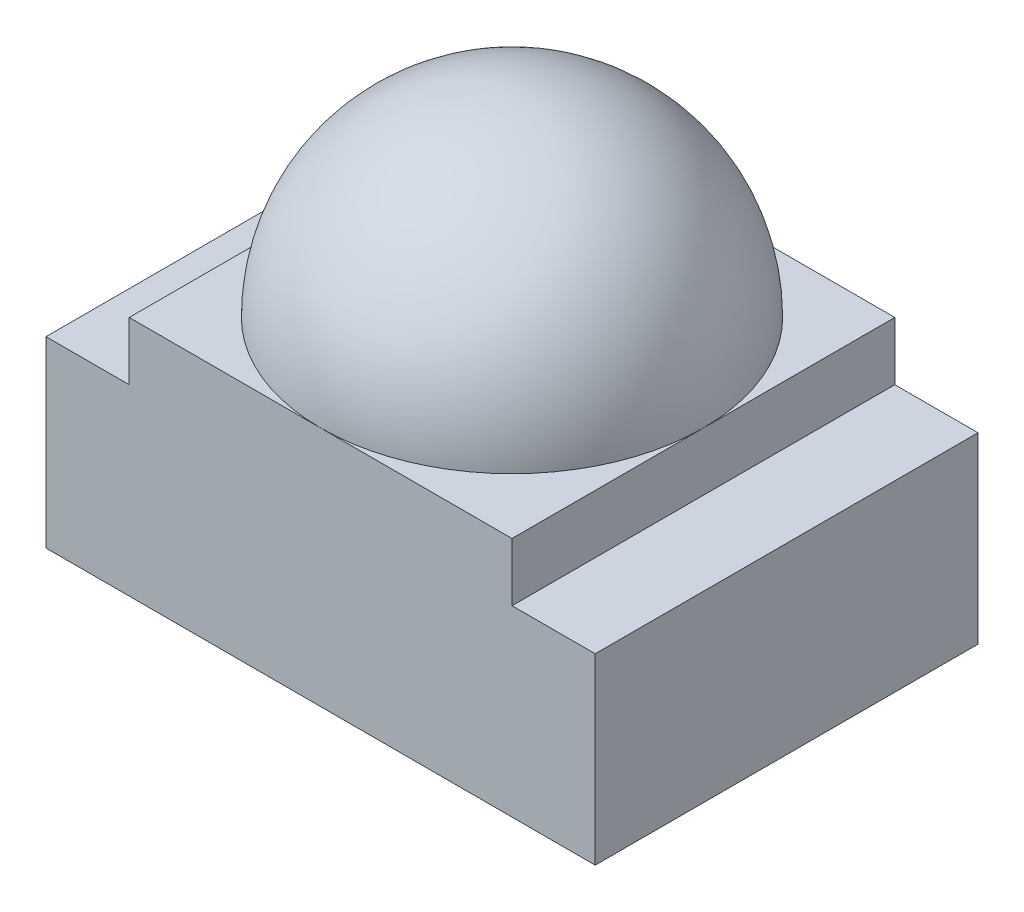
SolidWorks part; units mm, degrees
ref_plane "Front Plane" through (0, 0, 0) normal (0, 0, 1) x (1, 0, 0)
ref_plane "Top Plane" through (0, 0, 0) normal (0, 1, 0) x (1, 0, 0)
ref_plane "Right Plane" through (0, 0, 0) normal (1, 0, 0) x (0, 0, -1)
sketch "Sketch1" plane through (0, 0, 0) normal (0, 1, 0) x (1, 0, 0)
  line L1 (-16.5, 11.5) -> (16.5, 11.5)
  line L2 (-16.5, 11.5) -> (-16.5, -11.5)
  line L3 (-16.5, -11.5) -> (16.5, -11.5)
  line L4 (16.5, 11.5) -> (16.5, -11.5)
  line L5 (-16.5, 11.5) -> (16.5, -11.5) construction
  line L6 (-16.5, -11.5) -> (16.5, 11.5) construction
  point P0 (0, 0)
  dimension "D1" = 23
  dimension "D2" = 33
extrude "Boss-Extrude1" add sketch "Sketch1" along normal blind 1 and the other way blind 10
sketch "Sketch2" plane through (0, 1, 0) normal (0, 1, 0) x (1, 0, 0)
  line L1 (-11.5, 11.5) -> (11.5, 11.5)
  line L2 (-11.5, 11.5) -> (-11.5, -11.5)
  line L3 (-11.5, -11.5) -> (11.5, -11.5)
  line L4 (11.5, 11.5) -> (11.5, -11.5)
  line L5 (-11.5, 11.5) -> (11.5, -11.5) construction
  line L6 (-11.5, -11.5) -> (11.5, 11.5) construction
  point P0 (0, 0)
  dimension "D1" = 23
extrude "Boss-Extrude2" add sketch "Sketch2" along normal blind 3.5
ref_plane "Plane1" through (0, 0, 0) normal (0, 0, 1) x (1, 0, 0)
sketch "Sketch3" plane through (0, 0, 0) normal (0, 0, 1) x (1, 0, 0)
  line L0 (0, 16) -> (0, 4.5) construction
  line L1 (-11.5, 4.5) -> (11.5, 4.5) construction
  line L4 (0, 4.5) -> (11.5, 4.5)
  line L5 (0, 16) -> (0, 4.5)
  arc A0 (11.5, 4.5) -> (0, 16) centre (0, 4.5) ccw
revolve "Revolve1" add sketch "Sketch3" angle 360 about L0
